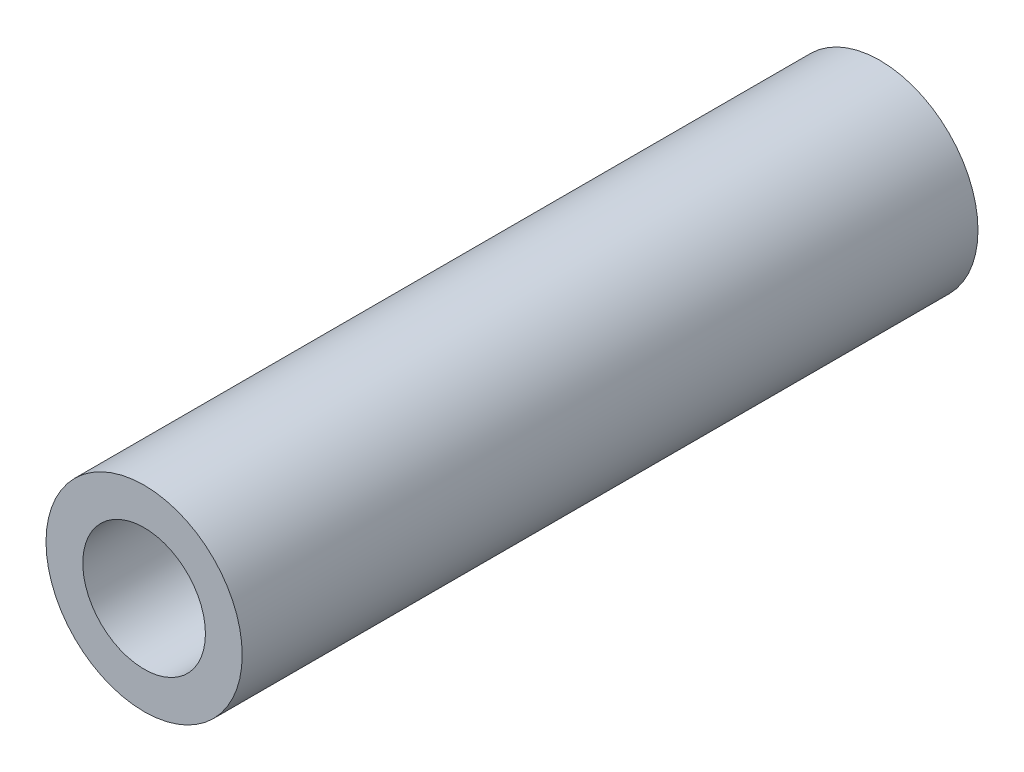
SolidWorks part; units mm, degrees
ref_plane "前视基准面" through (0, 0, 0) normal (0, 0, 1) x (1, 0, 0)
ref_plane "上视基准面" through (0, 0, 0) normal (0, 1, 0) x (1, 0, 0)
ref_plane "右视基准面" through (0, 0, 0) normal (1, 0, 0) x (0, 0, -1)
sketch "草图1" plane through (0, 0, 0) normal (0, 0, 1) x (1, 0, 0)
  circle A0 centre (0, 0) radius 4
  circle A1 centre (0, 0) radius 2.5
  point P5 (0.6212, 0)
  dimension "D1" = 5
  dimension "D2" = 8
extrude "凸台-拉伸1" add sketch "草图1" along normal mid plane 30
